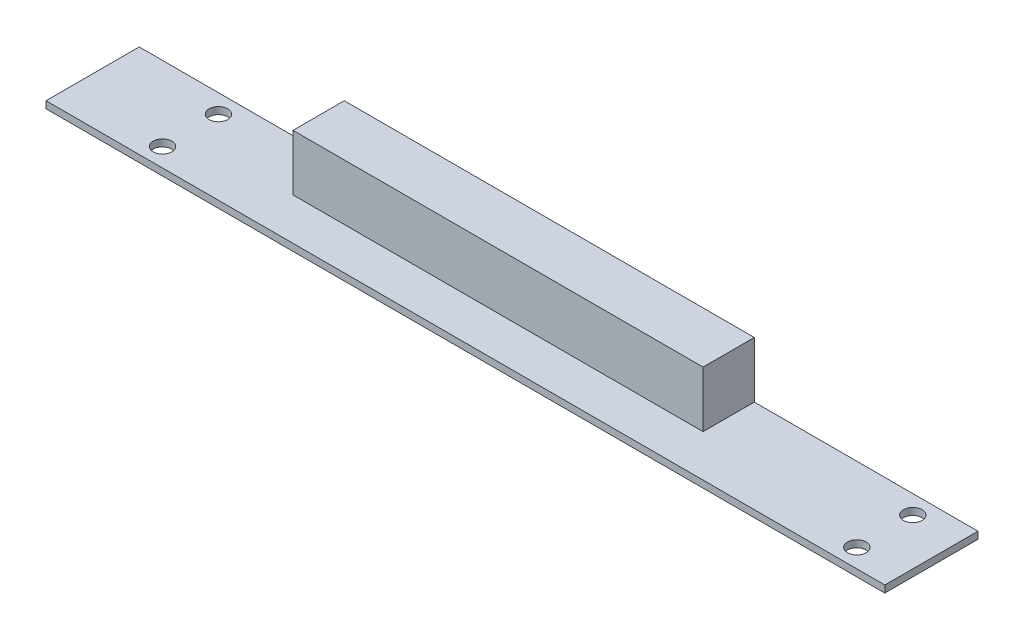
SolidWorks part; units mm, degrees
ref_plane "Front Plane" through (0, 0, 0) normal (0, 0, 1) x (1, 0, 0)
ref_plane "Top Plane" through (0, 0, 0) normal (0, 1, 0) x (1, 0, 0)
ref_plane "Right Plane" through (0, 0, 0) normal (1, 0, 0) x (0, 0, -1)
sketch "Sketch1" plane through (0, 0, 0) normal (0, 1, 0) x (1, 0, 0)
  line L0 (-1066.8589, 6) -> (48933.1411, 6) construction
  line L1 (-90, -10) -> (90, -10)
  line L2 (-90, -10) -> (-90, 10)
  line L3 (-90, 10) -> (90, 10)
  line L4 (90, -10) -> (90, 10)
  line L5 (-90, -10) -> (90, 10) construction
  line L6 (-90, 10) -> (90, -10) construction
  line L7 (-1061.1323, -6) -> (48938.8677, -6) construction
  line L8 (80, 6) -> (80, -6) construction
  line L9 (-69, 6) -> (-69, -6) construction
  circle A0 centre (-69, 6) radius 2
  circle A1 centre (-69, -6) radius 2
  circle A2 centre (80, 6) radius 2
  circle A3 centre (80, -6) radius 2
  point P0 (0, 0)
  dimension "D5" = 4
  dimension "D1" = 180
  dimension "D2" = 20
  dimension "D3" = 4
  dimension "D4" = 4
  dimension "D6" = 10
  dimension "D7" = 21
extrude "Boss-Extrude1" add sketch "Sketch1" along normal blind 1.5
sketch "Sketch2" plane through (0, 1.5, 0) normal (0, 1, 0) x (-1, 0, 0)
  line L0 (90, -10) -> (90, 10) construction
  line L1 (46, -10) -> (-42, -10)
  line L2 (46, -10) -> (46, 1)
  line L3 (46, 1) -> (-42, 1)
  line L4 (-42, -10) -> (-42, 1)
  line L5 (-90, 10) -> (-90, -10) construction
  line L6 (90, 10) -> (-90, 10) construction
  line L7 (-90, -10) -> (90, -10) construction
  point P6 (-90, 0)
  dimension "D1" = 44
  dimension "D2" = 48
  dimension "D3" = 9
extrude "Boss-Extrude2" add sketch "Sketch2" along normal blind 12
